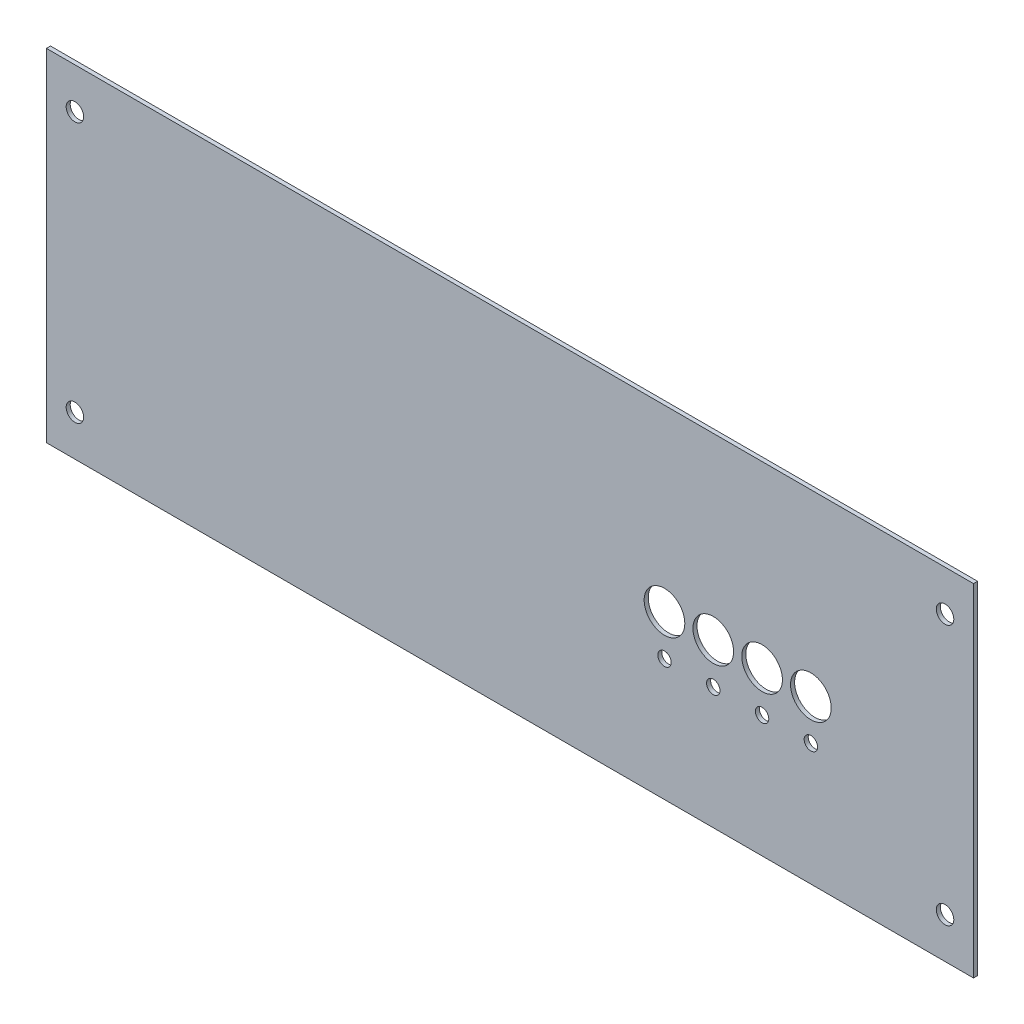
SolidWorks part; units mm, degrees
ref_plane "Спереди" through (0, 0, 0) normal (0, 0, 1) x (1, 0, 0)
ref_plane "Сверху" through (0, 0, 0) normal (0, 1, 0) x (1, 0, 0)
ref_plane "Справа" through (0, 0, 0) normal (1, 0, 0) x (0, 0, -1)
sketch "Эскиз1" plane through (0, 0, 0) normal (0, 0, 1) x (1, 0, 0)
  line L0 (0, 0) -> (58.061, 0) construction
  line L1 (0, 0) -> (0, 47.3035) construction
  line L2 (-15.7994, -2) -> (102.6804, -2) construction
  line L3 (-114, -42) -> (114, -42)
  line L4 (-114, -42) -> (-114, 42)
  line L5 (-114, 42) -> (114, 42)
  line L6 (114, -42) -> (114, 42)
  line L7 (74, 18.7167) -> (74, -25.7483) construction
  line L8 (62, -12) -> (62, -2) construction
  line L9 (50, -12) -> (50, -2) construction
  line L10 (38, -12) -> (38, -2) construction
  circle A0 centre (74, -2) radius 5
  circle A1 centre (74, -12) radius 1.65
  circle A2 centre (62, -2) radius 5
  circle A3 centre (62, -12) radius 1.65
  circle A4 centre (50, -2) radius 5
  circle A5 centre (50, -12) radius 1.65
  circle A6 centre (38, -2) radius 5
  circle A7 centre (38, -12) radius 1.65
  circle A8 centre (107, 32) radius 2.15
  circle A9 centre (-107, 32) radius 2.15
  circle A10 centre (-107, -32) radius 2.15
  circle A11 centre (107, -32) radius 2.15
  dimension "D4" = 10
  dimension "D5" = 3.3
  dimension "D6" = 10
  dimension "D8" = 10
  dimension "D9" = 10
  dimension "D10" = 10
  dimension "D14" = 4.3
  dimension "D15" = 10
  dimension "D16" = 7
  dimension "D1" = 84
  dimension "D2" = 228
  dimension "D3" = 80
  dimension "D7" = 40
  dimension "D11" = 12
  dimension "D12" = 12
  dimension "D13" = 12
extrude "Вытянуть1" add sketch "Эскиз1" along normal blind 1
